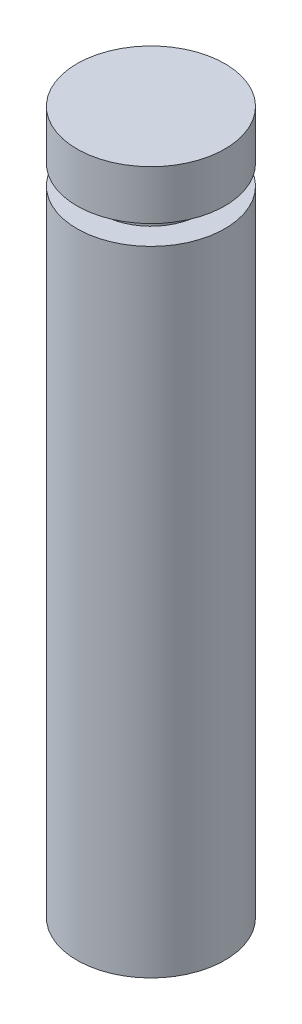
SolidWorks part; units mm, degrees
material "Alloy Steel"
ref_plane "Front Plane" through (0, 0, 0) normal (0, 0, 1) x (1, 0, 0)
ref_plane "Top Plane" through (0, 0, 0) normal (0, 1, 0) x (1, 0, 0)
ref_plane "Right Plane" through (0, 0, 0) normal (1, 0, 0) x (0, 0, -1)
sketch "Sketch1" plane through (0, 0, 0) normal (0, 0, 1) x (1, 0, 0)
  line L0 (3, 0) -> (3, 25.7)
  line L1 (3, 25.7) -> (2, 25.7)
  line L2 (2, 25.7) -> (2, 26.5)
  line L3 (2, 26.5) -> (3, 26.5)
  line L4 (3, 26.5) -> (3, 28.5)
  line L5 (3, 28.5) -> (0, 28.5)
  line L6 (0, 28.5) -> (0, 0)
  line L7 (0, 0) -> (3, 0)
  dimension "D1" = 3
  dimension "D2" = 0.8
  dimension "D3" = 26.5
  dimension "D4" = 2
  dimension "D5" = 2
revolve "Revolve1" add sketch "Sketch1" angle 360 about L6
